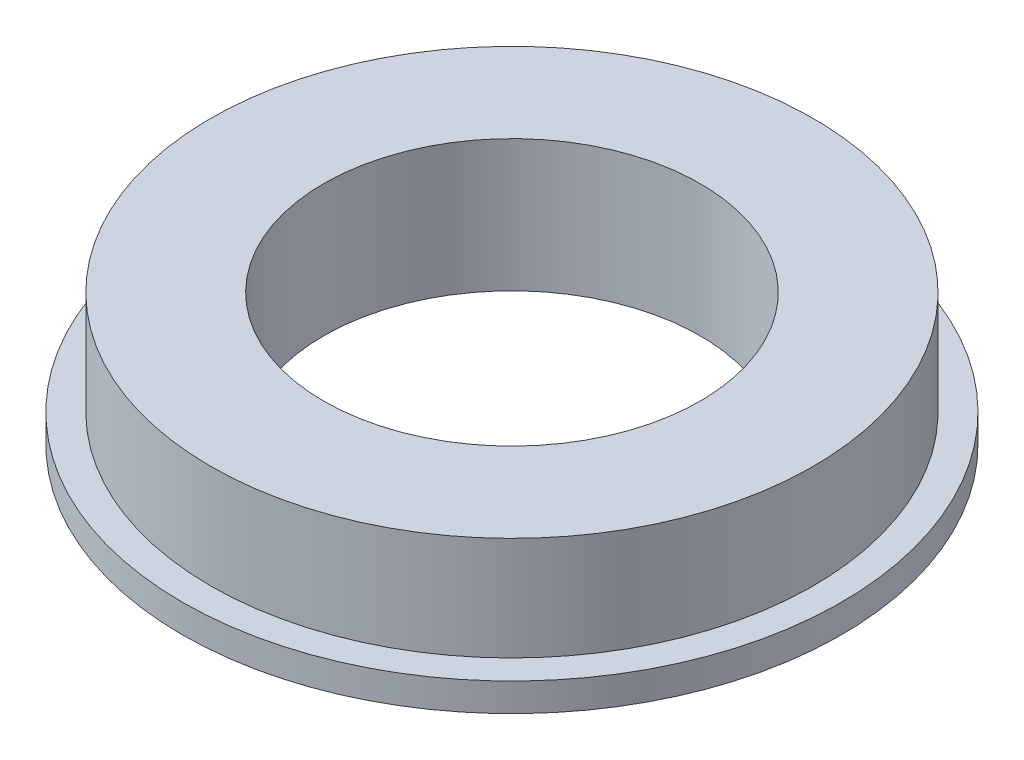
SolidWorks part; units mm, degrees
ref_plane "前视基准面" through (0, 0, 0) normal (0, 0, 1) x (1, 0, 0)
ref_plane "上视基准面" through (0, 0, 0) normal (0, 1, 0) x (1, 0, 0)
ref_plane "右视基准面" through (0, 0, 0) normal (1, 0, 0) x (0, 0, -1)
sketch "草图1" plane through (0, 0, 0) normal (0, 1, 0) x (1, 0, 0)
  circle A0 centre (0, 0) radius 10
  circle A1 centre (0, 0) radius 17.5
  dimension "D1" = 20
  dimension "D2" = 35
extrude "凸台-拉伸1" add sketch "草图1" along normal blind 1.5
sketch "草图2" plane through (0, 1.5, 0) normal (0, 1, 0) x (1, 0, 0)
  circle A0 centre (0, 0) radius 10
  circle A1 centre (0, 0) radius 16
  dimension "D1" = 20
  dimension "D2" = 32
extrude "凸台-拉伸2" add sketch "草图2" along normal blind 5.5
